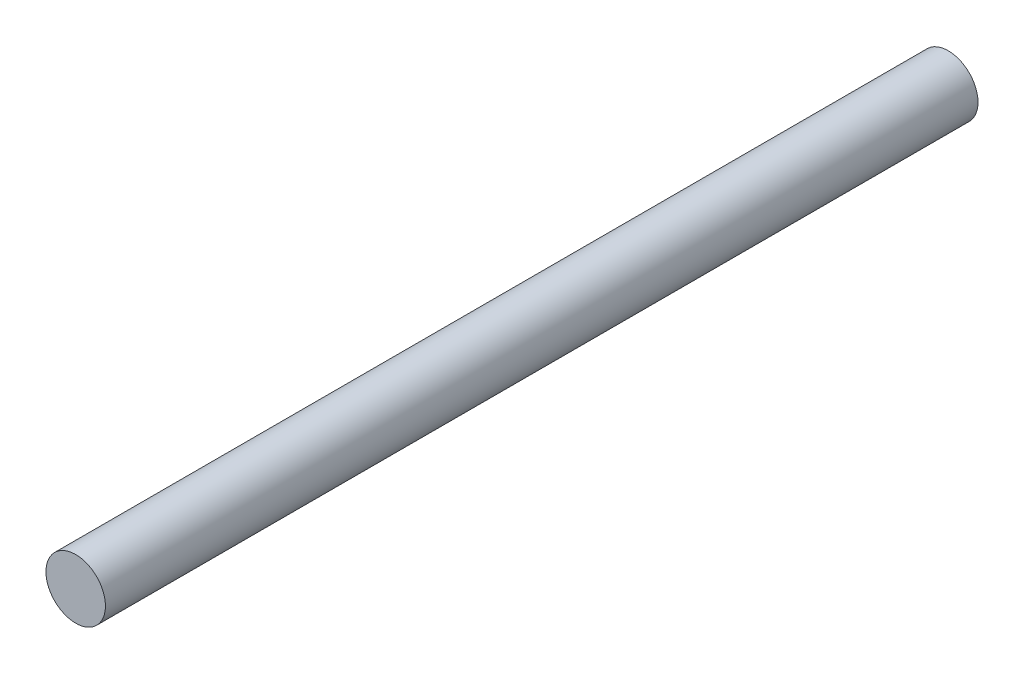
SolidWorks part; units mm, degrees
ref_plane "Alzado" through (0, 0, 0) normal (0, 0, 1) x (1, 0, 0)
ref_plane "Planta" through (0, 0, 0) normal (0, 1, 0) x (1, 0, 0)
ref_plane "Vista lateral" through (0, 0, 0) normal (1, 0, 0) x (0, 0, -1)
sketch "Croquis1" plane through (0, 0, 0) normal (0, 0, 1) x (1, 0, 0)
  circle A0 centre (0, 0) radius 1.5
  dimension "D1" = 3
extrude "Saliente-Extruir1" add sketch "Croquis1" along normal mid plane 44
